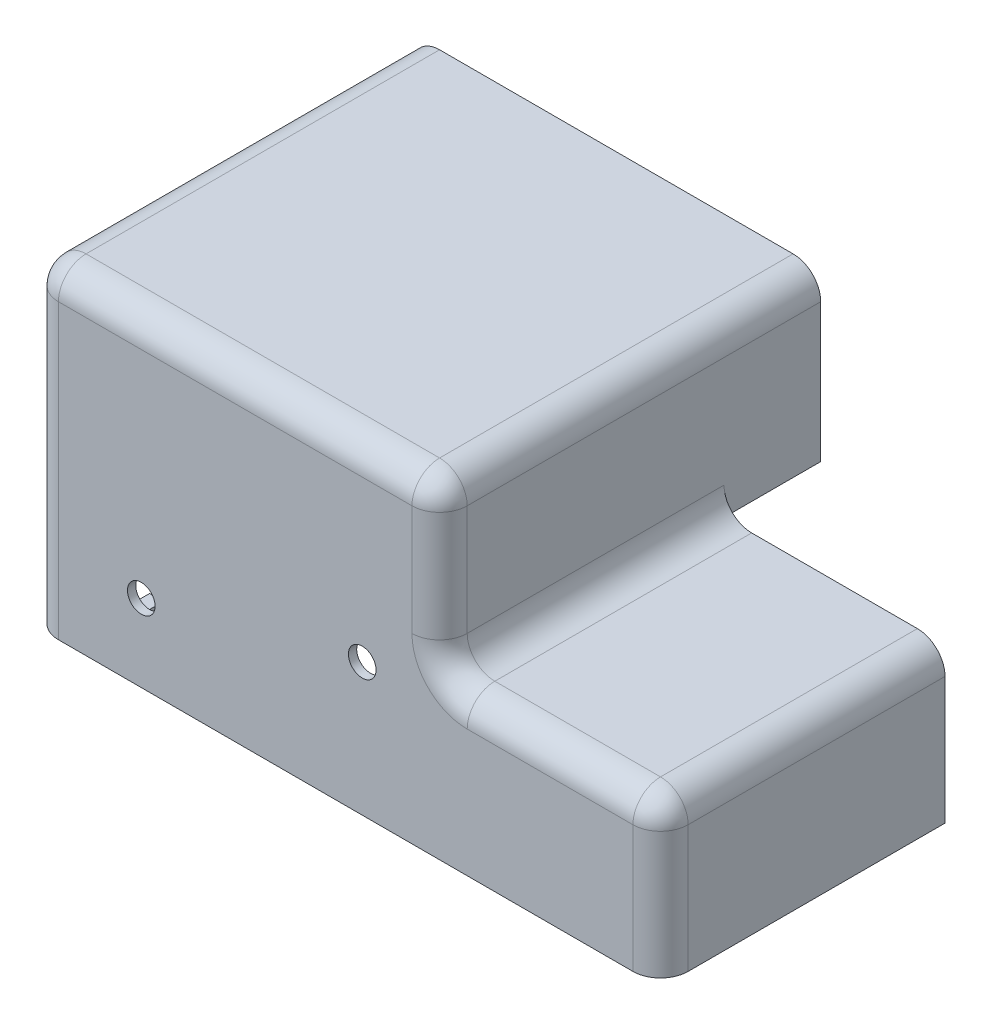
SolidWorks part; units mm, degrees
ref_plane "Front" through (0, 0, 0) normal (0, 0, 1) x (1, 0, 0)
ref_plane "Top" through (0, 0, 0) normal (0, 1, 0) x (1, 0, 0)
ref_plane "Right" through (0, 0, 0) normal (1, 0, 0) x (0, 0, -1)
sketch "Sketch1" plane through (0, 0, 0) normal (0, 0, 1) x (1, 0, 0)
  line L0 (-212, 8) -> (-220, 8)
  line L1 (-220, 8) -> (-220, 116)
  line L2 (-220, 116) -> (-72, 116)
  line L3 (-72, 116) -> (-72, 56)
  line L4 (-72, 56) -> (8, 56)
  line L5 (8, 56) -> (8, 0)
  line L6 (8, 0) -> (0, 0)
  line L7 (-212, 11) -> (-217, 11)
  line L8 (-217, 11) -> (-217, 113)
  line L9 (-217, 113) -> (-75, 113)
  line L10 (-75, 113) -> (-75, 53)
  line L11 (-75, 53) -> (5, 53)
  line L12 (5, 53) -> (5, 3)
  line L13 (5, 3) -> (0, 3)
  line L14 (-212, 8) -> (-212, 11)
  line L15 (0, 3) -> (0, 0)
  dimension "D2" = 148
  dimension "D3" = 5
  dimension "D4" = 50
  dimension "D5" = 80
  dimension "D6" = 60
  dimension "D7" = 5
  dimension "D8" = 8
  dimension "D1" = 3
extrude "Boss-Extrude1" add sketch "Sketch1" along normal blind 100
sketch "Sketch2" plane through (0, 0, 100) normal (0, 0, 1) x (1, 0, 0)
  line L0 (0, 0) -> (8, 0) construction
  line L1 (8, 0) -> (8, 56) construction
  line L2 (8, 56) -> (-72, 56) construction
  line L3 (-72, 56) -> (-72, 116) construction
  line L4 (-72, 116) -> (-220, 116) construction
  line L5 (-220, 116) -> (-220, 8) construction
  line L6 (0, 0) -> (8, 0)
  line L7 (8, 0) -> (8, 56)
  line L8 (8, 56) -> (-72, 56)
  line L9 (-72, 56) -> (-72, 116)
  line L10 (-72, 116) -> (-220, 116)
  line L11 (-220, 116) -> (-220, 8)
  line L12 (0, 0) -> (-220, 0)
  line L13 (-220, 0) -> (-220, 8)
extrude "Boss-Extrude2" add sketch "Sketch2" along normal blind 3
sketch "Sketch3" plane through (0, 0, 103) normal (0, 0, 1) x (1, 0, 0)
  line L0 (-220, 116) -> (-220, 0) construction
  line L1 (-220, 0) -> (8, 0) construction
  line L2 (8, 0) -> (8, 56) construction
  circle A0 centre (-180, 28) radius 5
  circle A1 centre (-100, 48) radius 5
  dimension "D1" = 10
  dimension "D2" = 10
  dimension "D3" = 40
  dimension "D4" = 28
  dimension "D5" = 48
  dimension "D6" = 108
extrude "Cut-Extrude1" cut sketch "Sketch3" against normal blind 3
sketch "Sketch4" plane through (0, 0, 100) normal (0, 0, -1) x (-1, 0, 0)
  line L0 (205.9316, 8) -> (123.2438, 8) construction
  line L2 (217, 11) -> (217, 113) construction
  line L3 (190, 8) -> (195, 8)
  line L4 (190, 8) -> (190, 13)
  line L5 (190, 13) -> (195, 13)
  line L6 (195, 8) -> (195, 13)
  line L7 (-5, 53) -> (-5, 3) construction
  line L8 (24.8, 8) -> (84.8, 8)
  line L9 (24.8, 8) -> (24.8, 13)
  line L10 (24.8, 13) -> (84.8, 13)
  line L11 (84.8, 8) -> (84.8, 13)
  line L12 (220, 8) -> (212, 8) construction
  point P16 (205.9316, 11)
  dimension "D1" = 27
  dimension "D2" = 5
  dimension "D3" = 5
  dimension "D4" = 60
  dimension "D5" = 5
  dimension "D6" = 89.8
extrude "Boss-Extrude3" add sketch "Sketch4" along normal blind 15
sketch "Sketch5" plane through (0, 0, 0) normal (0, 0, -1) x (-1, 0, 0)
  line L1 (72, 116) -> (220, 116)
  line L5 (217, 11) -> (217, 113) construction
  line L6 (217, 113) -> (75, 113) construction
  line L7 (75, 113) -> (75, 53) construction
  line L8 (72, 56) -> (72, 116) construction
  line L10 (217, 81) -> (217, 113)
  line L11 (217, 113) -> (75, 113)
  line L12 (75, 113) -> (75, 53)
  line L13 (72, 56) -> (72, 116)
  line L14 (217, 81) -> (220, 81)
  line L15 (72, 56) -> (72, 53)
  line L16 (75, 53) -> (-5, 53) construction
  line L17 (72, 53) -> (75, 53)
  line L18 (220, 116) -> (220, 81)
  dimension "D1" = 35
extrude "Boss-Extrude4" add sketch "Sketch5" along normal blind 35
fillet "Fillet2" radius 10 13 edges at (-32, 56, 103) (-220, 58, 103) (8, 28, 103) (-72, 86, 103) (-146, 116, 103) (-220, 116, 34) (-217, 113, 32.5) (5, 53, 50) (8, 56, 51.5) (-75, 53, 32.5) (-75, 113, 32.5) (-72, 56, 51.5) (-72, 116, 34)
